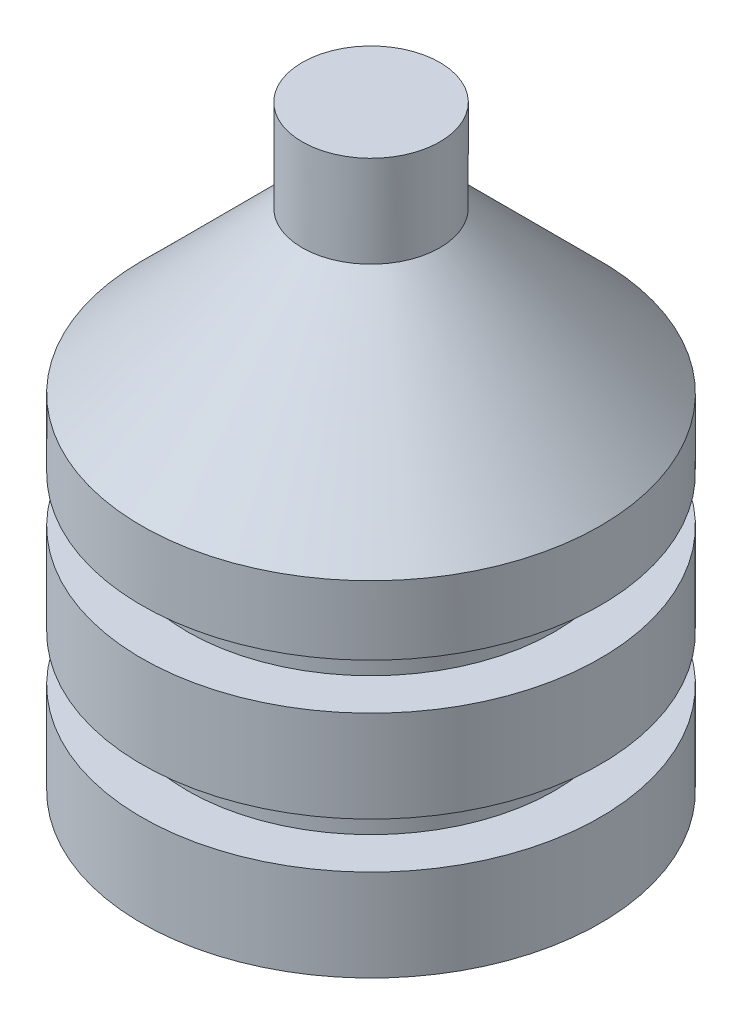
SolidWorks part; units mm, degrees
ref_plane "Front Plane" through (0, 0, 0) normal (0, 0, 1) x (1, 0, 0)
ref_plane "Top Plane" through (0, 0, 0) normal (0, 1, 0) x (1, 0, 0)
ref_plane "Right Plane" through (0, 0, 0) normal (1, 0, 0) x (0, 0, -1)
sketch "Sketch3" plane through (0, 0, 0) normal (0, 0, 1) x (1, 0, 0)
  line L0 (0, 113.5937) -> (0, -16.4063)
  line L1 (0, 113.5937) -> (-15, 113.5937)
  line L2 (-15, 113.5937) -> (-15, 93.5937)
  line L3 (-15, 93.5937) -> (-50, 58.5937)
  line L4 (-50, 58.5937) -> (-50, 43.5937)
  line L5 (-50, 43.5937) -> (-40, 43.5937)
  line L6 (-40, 43.5937) -> (-40, 28.5937)
  line L7 (-40, 28.5937) -> (-40, 43.5937)
  line L8 (-40, 13.5937) -> (-40, 3.5937)
  line L9 (-40, 3.5937) -> (-50, 3.5937)
  line L10 (-40, 43.5937) -> (-40, 33.5937)
  line L11 (-40, 33.5937) -> (-50, 33.5937)
  line L12 (-50, 33.5937) -> (-50, 13.5937)
  line L13 (-50, 13.5937) -> (-40, 13.5937)
  line L14 (-50, 3.5937) -> (-50, -16.4063)
  line L15 (-50, -16.4063) -> (0, -16.4063)
  dimension "D1" = 15
  dimension "D3" = 20
  dimension "D4" = 15
  dimension "D6" = 10
  dimension "D9" = 20
  dimension "D10" = 10
  dimension "D11" = 10
  dimension "D12" = 20
revolve "Revolve4" add sketch "Sketch3" angle 360 about L0
